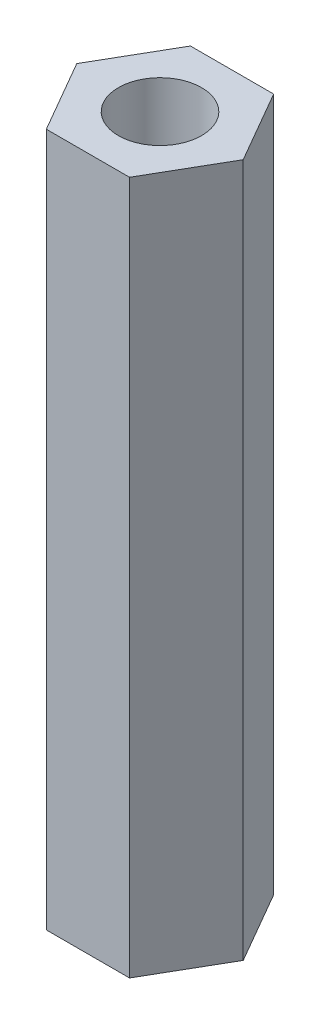
SolidWorks part; units mm, degrees
ref_plane "Front Plane" through (0, 0, 0) normal (0, 0, 1) x (1, 0, 0)
ref_plane "Top Plane" through (0, 0, 0) normal (0, 1, 0) x (1, 0, 0)
ref_plane "Right Plane" through (0, 0, 0) normal (1, 0, 0) x (0, 0, -1)
sketch "Sketch1" plane through (0, 0, 0) normal (0, 1, 0) x (1, 0, 0)
  line L0 (-3, 0) -> (3, 0) construction
  line L1 (-1.5, 2.5981) -> (-3, 0)
  line L2 (-3, 0) -> (-1.5, -2.5981)
  line L3 (-1.5, -2.5981) -> (1.5, -2.5981)
  line L4 (1.5, -2.5981) -> (3, 0)
  line L5 (3, 0) -> (1.5, 2.5981)
  line L6 (1.5, 2.5981) -> (-1.5, 2.5981)
  circle A0 centre (0, 0) radius 1.5
  circle A2 centre (0, 0) radius 2.5981 construction
  dimension "D1" = 3
  dimension "D2" = 3
extrude "Boss-Extrude1" add sketch "Sketch1" along normal blind 25
